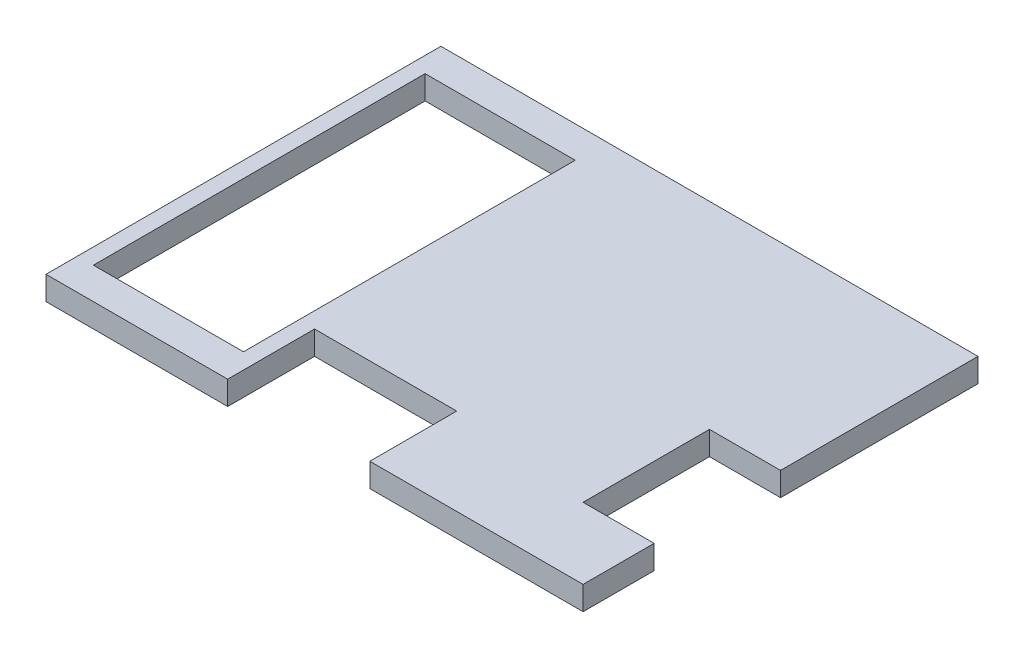
SolidWorks part; units mm, degrees
ref_plane "Front Plane" through (0, 0, 0) normal (0, 0, 1) x (1, 0, 0)
ref_plane "Top Plane" through (0, 0, 0) normal (0, 1, 0) x (1, 0, 0)
ref_plane "Right Plane" through (0, 0, 0) normal (1, 0, 0) x (0, 0, -1)
sketch "Sketch1" plane through (0, 0, 0) normal (0, 1, 0) x (1, 0, 0)
  line L0 (-34, -25) -> (-11, -25)
  line L1 (-34, 25) -> (34, 25)
  line L2 (-34, 25) -> (-34, -25)
  line L3 (7, -25) -> (34, -25)
  line L4 (34, 25) -> (34, 0)
  line L5 (-34, 25) -> (34, -25) construction
  line L6 (-34, -25) -> (34, 25) construction
  line L7 (-32, 21) -> (-13, 21)
  line L8 (-32, 21) -> (-32, -21)
  line L9 (-32, -21) -> (-13, -21)
  line L10 (-13, 21) -> (-13, -21)
  line L11 (-32, 21) -> (-13, -21) construction
  line L12 (-32, -21) -> (-13, 21) construction
  line L13 (34, -16) -> (34, -25)
  line L14 (7, -25) -> (7, -14)
  line L15 (7, -14) -> (-11, -14)
  line L16 (-11, -25) -> (-11, -14)
  line L17 (34, 0) -> (25, 0)
  line L19 (34, -16) -> (25, -16)
  line L20 (25, 0) -> (25, -16)
  point P0 (0, 0)
  point P6 (-22.5, 0)
  dimension "D1" = 68
  dimension "D2" = 50
  dimension "D3" = 25
  dimension "D4" = 4
  dimension "D5" = 2
  dimension "D6" = 19
  dimension "D7" = 23
  dimension "D8" = 9
  dimension "D9" = 9
  dimension "D10" = 27
  dimension "D11" = 11
extrude "Boss-Extrude1" add sketch "Sketch1" along normal blind 3
